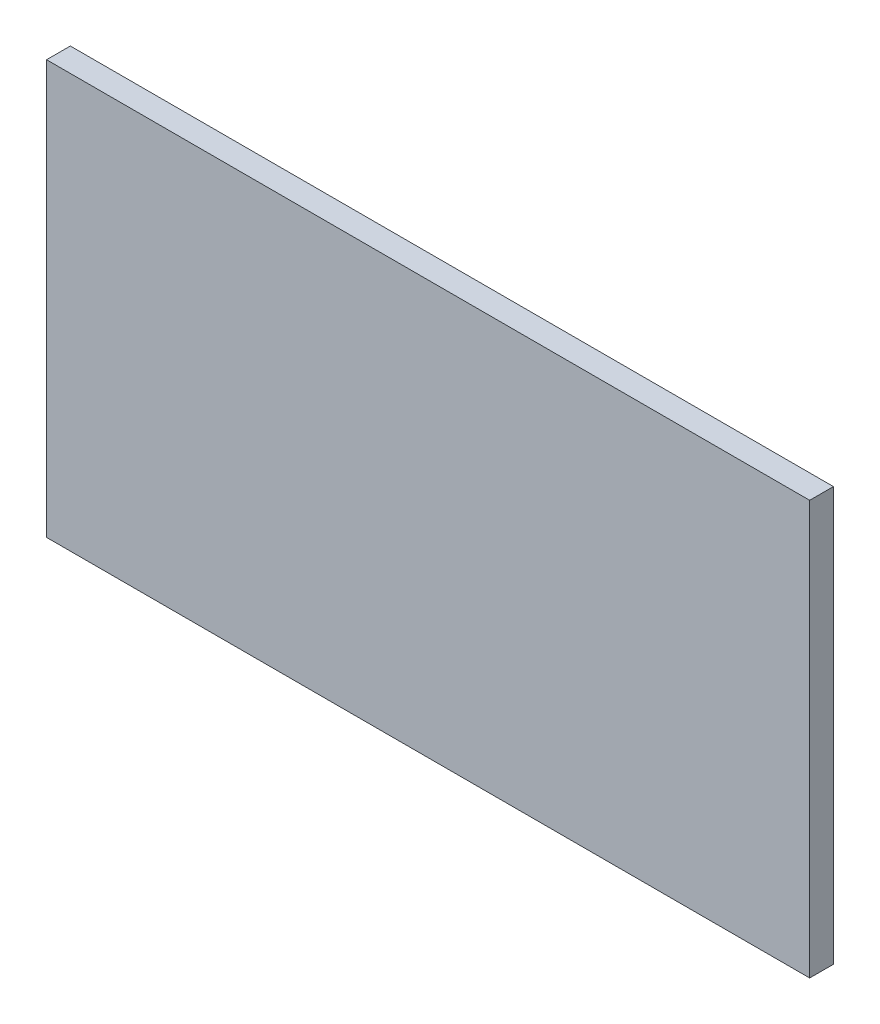
SolidWorks part; units mm, degrees
ref_plane "前基準面" through (0, 0, 0) normal (0, 0, 1) x (1, 0, 0)
ref_plane "上基準面" through (0, 0, 0) normal (0, 1, 0) x (1, 0, 0)
ref_plane "右基準面" through (0, 0, 0) normal (1, 0, 0) x (0, 0, -1)
sketch "草圖1" plane through (0, 0, 0) normal (0, 0, 1) x (1, 0, 0)
  line L1 (-21.5461, 26.941) -> (60.0203, 26.941)
  line L2 (-21.5461, 26.941) -> (-21.5461, -17.2794)
  line L3 (-21.5461, -17.2794) -> (60.0203, -17.2794)
  line L4 (60.0203, 26.941) -> (60.0203, -17.2794)
extrude "填料-伸長1" add sketch "草圖1" along normal blind 2.54
